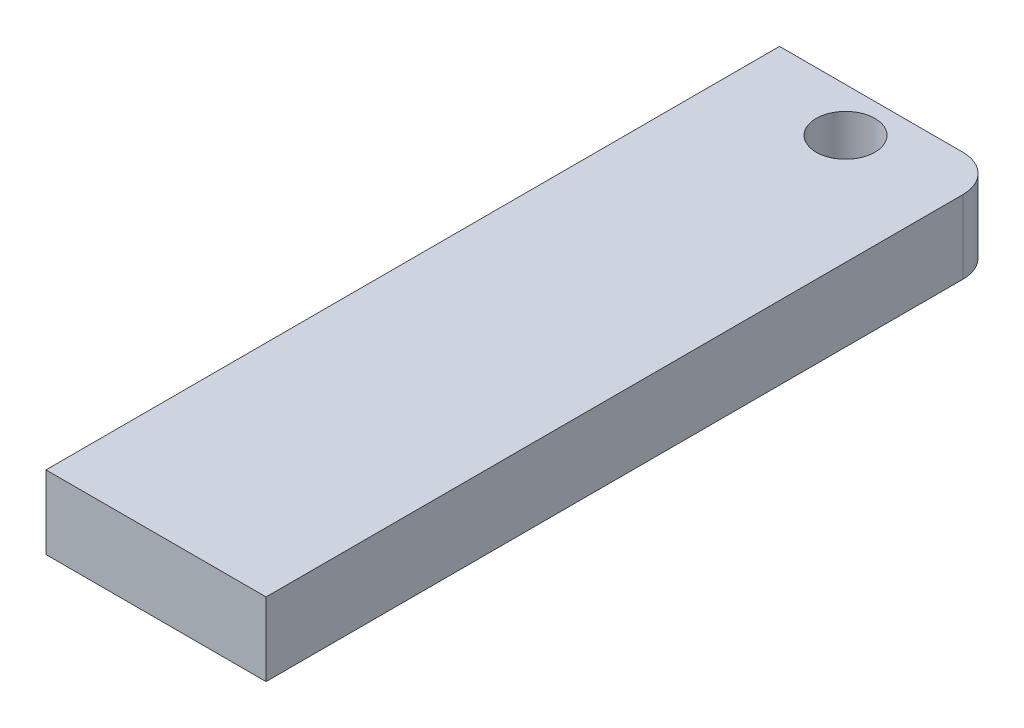
SolidWorks part; units mm, degrees
ref_plane "Front Plane" through (0, 0, 0) normal (0, 0, 1) x (1, 0, 0)
ref_plane "Top Plane" through (0, 0, 0) normal (0, 1, 0) x (1, 0, 0)
ref_plane "Right Plane" through (0, 0, 0) normal (1, 0, 0) x (0, 0, -1)
sketch "Sketch2" plane through (0, 0, 0) normal (0, 0, 1) x (1, 0, 0)
  line L1 (0, 0) -> (30, 0)
  line L2 (0, 0) -> (0, 10)
  line L3 (0, 10) -> (30, 10)
  line L4 (30, 0) -> (30, 10)
  dimension "D1" = 10
  dimension "D2" = 30
extrude "Boss-Extrude1" add sketch "Sketch2" along normal blind 100
sketch "Sketch3" plane through (0, 10, 0) normal (0, 1, 0) x (1, 0, 0)
  line L0 (30, 0) -> (0, 0) construction
  circle A0 centre (15, -6) radius 4
  point P2 (15, 0)
  point P3 (0, 0)
  point P6 (0, 0)
  dimension "D1" = 8
  dimension "D2" = 6
extrude "Cut-Extrude1" cut sketch "Sketch3" against normal blind 30
fillet "Fillet1" radius 5 1 edges at (30, 5, 0)
